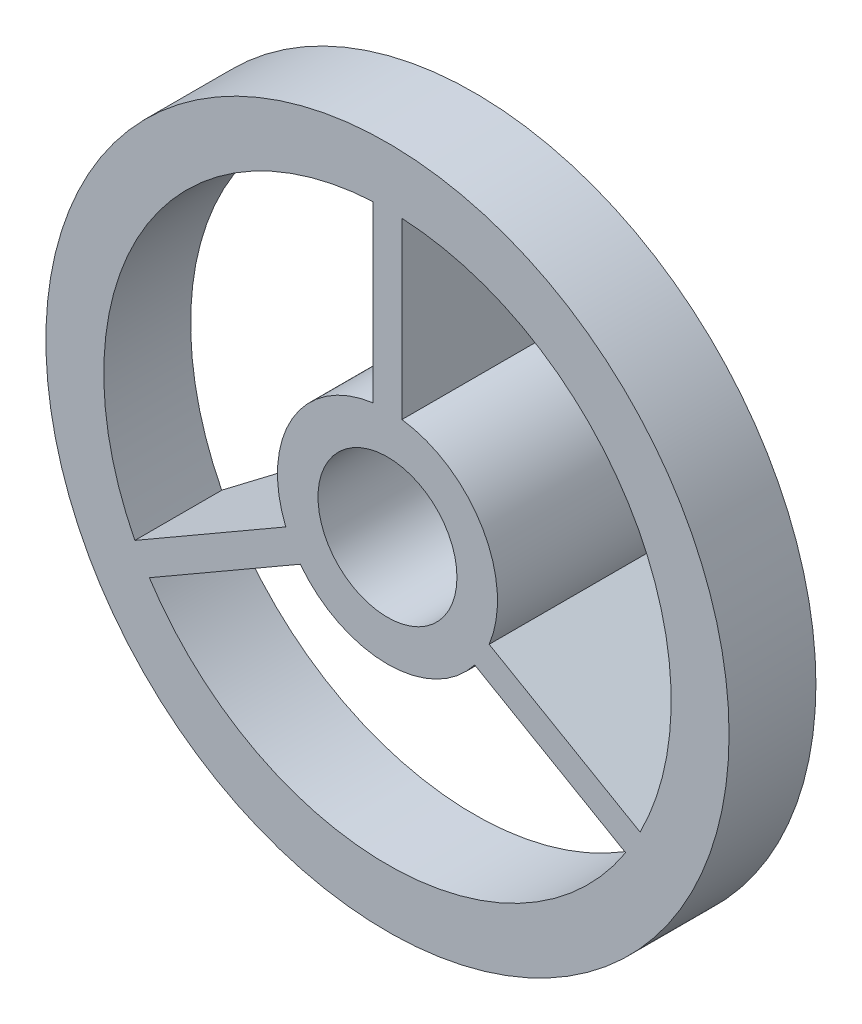
SolidWorks part; units mm, degrees
ref_plane "Front Plane" through (0, 0, 0) normal (0, 0, 1) x (1, 0, 0)
ref_plane "Top Plane" through (0, 0, 0) normal (0, 1, 0) x (1, 0, 0)
ref_plane "Right Plane" through (0, 0, 0) normal (1, 0, 0) x (0, 0, -1)
sketch "Sketch2" plane through (0, 0, 0) normal (0, 0, 1) x (1, 0, 0)
  circle A0 centre (0, 0) radius 1.2
  circle A1 centre (0, 0) radius 1.9
  dimension "D1" = 2.4
  dimension "D2" = 0.7
extrude "Boss-Extrude1" add sketch "Sketch2" along normal blind 3.5
sketch "Sketch3" plane through (0, 0, 3.5) normal (0, 0, 1) x (1, 0, 0)
  circle A1 centre (0, 0) radius 5.9
  circle A2 centre (0, 0) radius 4.9
  circle A3 centre (0, 0) radius 4.9
  dimension "D1" = 3
  dimension "D2" = 1
extrude "Boss-Extrude2" add sketch "Sketch3" against normal blind 1.5 separate body
sketch "Sketch4" plane through (0, 0, 0) normal (1, 0, 0) x (0, 0, -1)
  line L0 (-3.5, 1.9) -> (0, 1.9) construction
  line L1 (-3.5, 1.9) -> (-3.5, -1.9) construction
  line L2 (-3.5, 4.9) -> (-3.5, -4.9) construction
  line L3 (0, -1.9) -> (0, 1.9) construction
  line L4 (0, 1.9) -> (-2, 4.9)
  line L5 (-2, -4.9) -> (-2, 4.9) construction
  line L6 (-2, -5.9) -> (-2, 5.9) construction
  line L7 (-2, 4.9) -> (-3.5, 4.9)
  line L8 (-3.5, 4.9) -> (-3.5, 1.9)
  line L9 (-3.5, 1.7) -> (0, 1.7)
  line L10 (-3.5, 1.9) -> (-3.5, 1.7)
  line L11 (0, 1.7) -> (0, 1.9)
  dimension "D1" = 0.2
extrude "Boss-Extrude3" add sketch "Sketch4" along normal mid plane 0.5
pattern_circular "CirPattern1" count 3 over 360 about axis through (0, 0, 0) along (0, 0, 1) of "Boss-Extrude3"
